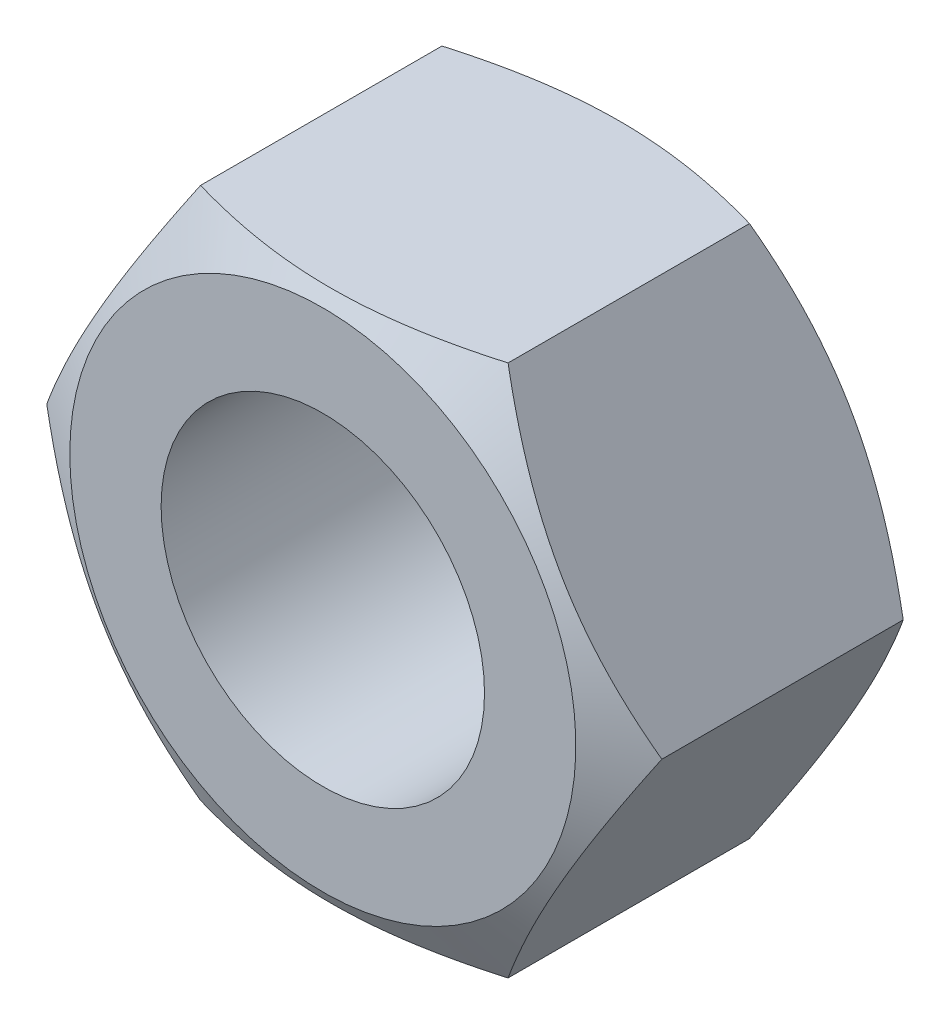
SolidWorks part; units mm, degrees
ref_plane "Plane1" through (0, 0, 0) normal (0, 0, 1) x (1, 0, 0)
ref_plane "Plane2" through (0, 0, 0) normal (0, 1, 0) x (1, 0, 0)
ref_plane "Plane3" through (0, 0, 0) normal (1, 0, 0) x (0, 0, -1)
sketch "BaseNutSke" plane through (0, 0, 0) normal (0, 0, 1) x (1, 0, 0)
  line L6 (4.0415, -7) -> (-4.0415, -7)
  line L7 (4.0415, 7) -> (-4.0415, 7)
  line L8 (4.0415, -7) -> (8.0829, 0)
  line L9 (8.0829, 0) -> (4.0415, 7)
  line L10 (-4.0415, 7) -> (-8.0829, 0)
  line L11 (-8.0829, 0) -> (-4.0415, -7)
  circle A0 centre (0, 0) radius 4.25 construction
  circle A1 centre (0, 0) radius 8.0829 construction
  circle A2 centre (0, 0) radius 4.25
  dimension "Tap_drill" = 8.5
  dimension "Diameter" = 8.5
  dimension "Width_flats" = 14
extrude "BaseNut" add sketch "BaseNutSke" against normal blind 8
cosmetic thread "ThreadCosmetic" parameters "Thread_major"=10
ref_plane "Plane4" through (0, 0, -4) normal (0, 0, -1) x (-1, 0, 0)
sketch "Sketch6" plane through (0, 0, -8) normal (0, 0, -1) x (-1, 0, 0)
  circle A0 centre (0, 0) radius 6.65
  dimension "D1" = 13.3
extrude "Cut-Extrude2" cut sketch "Sketch6" against normal through all draft 60 flip side to cut
mirror "Mirror1" about plane through (0, 0, -4) normal (0, 0, -1) of "Cut-Extrude2"
equation "\"D1@Sketch3\" = \"Width_flats@BaseNutSke\" /2"
equation "' \"Num_threads@ThdSchPat\" = \"Num_threads@ThdSchPat\" - sgn( \"Num_threads@ThdSchPat\" - 1) '---chamfered tips only---"
equation "\"D1@Sketch6\" = 0.95 * \"Width_flats@BaseNutSke\""
